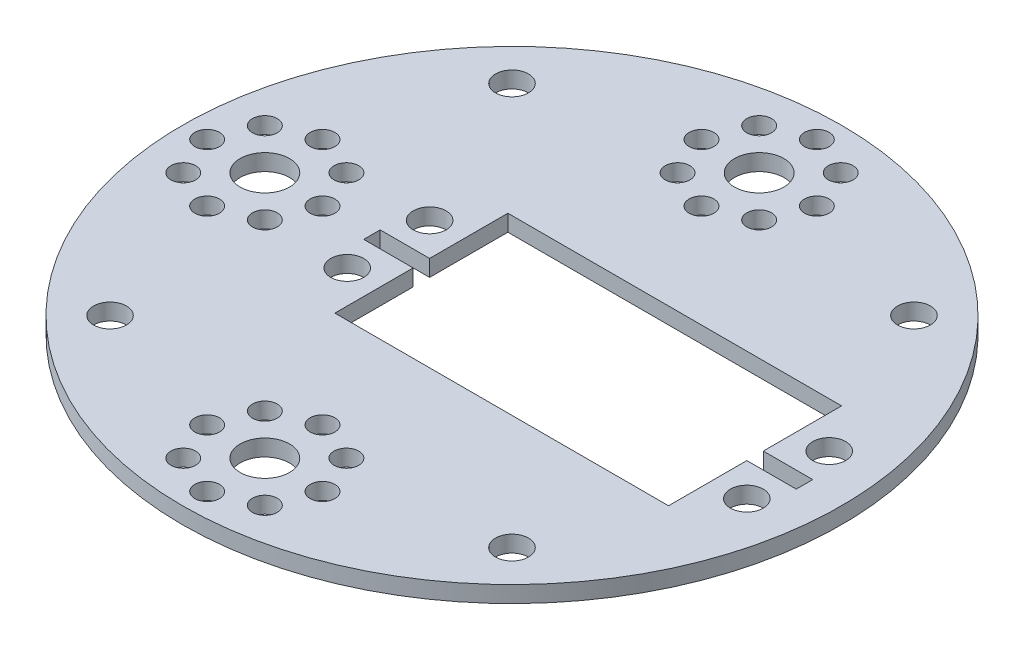
SolidWorks part; units mm, degrees
ref_plane "前视基准面" through (0, 0, 0) normal (0, 0, 1) x (1, 0, 0)
ref_plane "上视基准面" through (0, 0, 0) normal (0, 1, 0) x (1, 0, 0)
ref_plane "右视基准面" through (0, 0, 0) normal (1, 0, 0) x (0, 0, -1)
other "Configuration Table"
sketch "草图1" plane through (0, 0, 0) normal (0, 1, 0) x (1, 0, 0)
  line L0 (0, 40) -> (0, -40) construction
  line L1 (-24.395, 24.395) -> (24.395, 24.395) construction
  line L2 (-24.395, 24.395) -> (-24.395, -24.395) construction
  line L3 (-24.395, -24.395) -> (24.395, -24.395) construction
  line L4 (24.395, 24.395) -> (24.395, -24.395) construction
  line L5 (-24.395, 24.395) -> (24.395, -24.395) construction
  line L6 (-24.395, -24.395) -> (24.395, 24.395) construction
  line L7 (-40, 0) -> (-17, 0) construction
  line L8 (-30, 0) -> (-17, 0)
  line L9 (-11, -1) -> (-11, -10.5)
  line L10 (-11, -10.5) -> (29.5, -10.5)
  line L11 (29.5, -10.5) -> (29.5, -1)
  line L12 (-17, 1) -> (-17, -1)
  line L13 (-17, -1) -> (-11, -1)
  line L14 (-11, 0) -> (40, 0) construction
  line L15 (29.5, -1) -> (35.5, -1)
  line L16 (35.5, -1) -> (35.5, 1)
  line L17 (29.5, 1) -> (35.5, 1)
  line L18 (29.5, 10.5) -> (29.5, 1)
  line L19 (-11, 10.5) -> (29.5, 10.5)
  line L20 (-11, 1) -> (-11, 10.5)
  line L21 (-17, 1) -> (-11, 1)
  circle A0 centre (0, 0) radius 40
  circle A1 centre (-24.395, 24.395) radius 2
  circle A2 centre (24.395, 24.395) radius 2
  circle A3 centre (24.395, -24.395) radius 2
  circle A4 centre (-24.395, -24.395) radius 2
  circle A5 centre (0, -30) radius 3
  circle A6 centre (0, -23) radius 1.5
  circle A7 centre (4.9497, -25.0503) radius 1.5
  circle A8 centre (7, -30) radius 1.5
  circle A9 centre (4.9497, -34.9497) radius 1.5
  circle A10 centre (0, -37) radius 1.5
  circle A11 centre (-4.9497, -34.9497) radius 1.5
  circle A12 centre (-7, -30) radius 1.5
  circle A13 centre (-4.9497, -25.0503) radius 1.5
  circle A14 centre (0, 30) radius 3
  circle A15 centre (4.9497, 25.0503) radius 1.5
  circle A16 centre (7, 30) radius 1.5
  circle A17 centre (4.9497, 34.9497) radius 1.5
  circle A18 centre (0, 37) radius 1.5
  circle A19 centre (-4.9497, 34.9497) radius 1.5
  circle A20 centre (-7, 30) radius 1.5
  circle A21 centre (-4.9497, 25.0503) radius 1.5
  circle A22 centre (0, 23) radius 1.5
  circle A23 centre (-30, 0) radius 3
  circle A24 centre (-23, 0) radius 1.5
  circle A25 centre (-25.0503, -4.9497) radius 1.5
  circle A26 centre (-30, -7) radius 1.5
  circle A27 centre (-34.9497, -4.9497) radius 1.5
  circle A28 centre (-37, 0) radius 1.5
  circle A29 centre (-34.9497, 4.9497) radius 1.5
  circle A30 centre (-30, 7) radius 1.5
  circle A31 centre (-25.0503, 4.9497) radius 1.5
  circle A32 centre (-15, -5) radius 2
  circle A33 centre (33.5, -5) radius 2
  circle A34 centre (33.5, 5) radius 2
  circle A35 centre (-15, 5) radius 2
  point P17 (0, 0)
  point P37 (0, -30)
  point P76 (-30, 0)
  point P91 (35.5, 0)
  dimension "D1" = 80
  dimension "D4" = 4
  dimension "D7" = 6
  dimension "D9" = 3
  dimension "D11" = 6
  dimension "D13" = 3
  dimension "D26" = 4
  dimension "D27" = 4
  dimension "D2" = 48.79
  dimension "D3" = 48.79
  dimension "D6" = 10
  dimension "D8" = 7
  dimension "D12" = 10
  dimension "D14" = 7
  dimension "D16" = 19
  dimension "D17" = 10.5
  dimension "D18" = 40.5
  dimension "D19" = 1
  dimension "D20" = 6
  dimension "D21" = 6
  dimension "D22" = 4
  dimension "D23" = 5
  dimension "D24" = 5
  dimension "D25" = 4
  dimension "D5" = 4
  dimension "D10" = 8
  dimension "D15" = 8
extrude "凸台-拉伸1" add sketch "草图1" along normal blind 2
